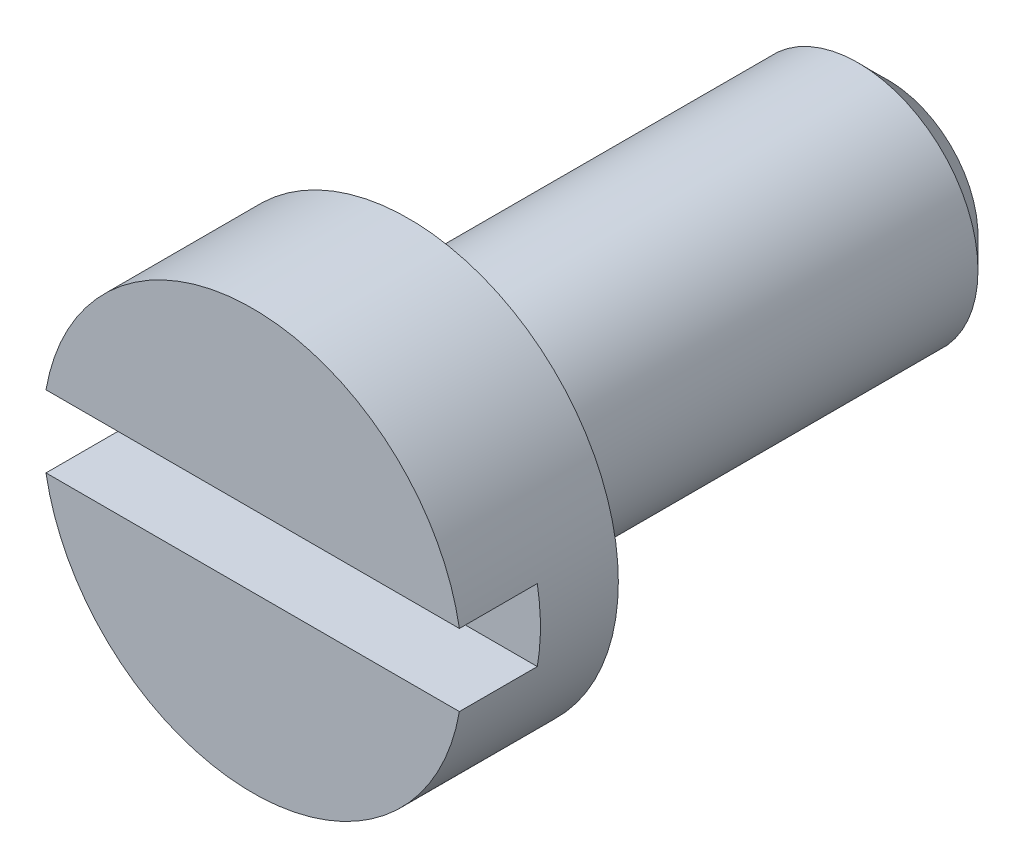
SolidWorks part; units mm, degrees
material "Простая углеродистая сталь"
ref_plane "Спереди" through (0, 0, 0) normal (0, 0, 1) x (1, 0, 0)
ref_plane "Сверху" through (0, 0, 0) normal (0, 1, 0) x (1, 0, 0)
ref_plane "Справа" through (0, 0, 0) normal (1, 0, 0) x (0, 0, -1)
sketch "Эскиз1" plane through (0, 0, 0) normal (0, 0, 1) x (1, 0, 0)
  circle A0 centre (0, 0) radius 3.5
  dimension "D" = 7
extrude "Бобышка-Вытянуть1" add sketch "Эскиз1" along normal blind 2.6
sketch "Эскиз2" plane through (0, 0, 0) normal (0, 0, -1) x (-1, 0, 0)
  circle A0 centre (0, 0) radius 2
  dimension "d'" = 4
extrude "Бобышка-Вытянуть2" add sketch "Эскиз2" along normal blind 8
cosmetic thread "Условное изображение резьбы1" parameters "D2"=3.22
chamfer "Фаска1" distance 0.5 angle 45 1 edges at (-2, 0, -8)
sketch "Эскиз3" plane through (0, 0, 0) normal (1, 0, 0) x (0, 0, -1)
  line L0 (-2.6, 3.5) -> (-2.6, -3.5) construction
  line L1 (-1.3, -0.6) -> (-2.6, -0.6)
  line L2 (-1.3, -0.6) -> (-1.3, 0.6)
  line L3 (-1.3, 0.6) -> (-2.6, 0.6)
  line L4 (-2.6, -0.6) -> (-2.6, 0.6)
  point P6 (-1.3, 0)
  dimension "D1" = 1.2
  dimension "D2" = 1.3
extrude "Вырез-Вытянуть1" cut sketch "Эскиз3" against normal through all and the other way through all
equation "\"D2@Эскиз3\"=\"k@Бобышка-Вытянуть1\"/2"
